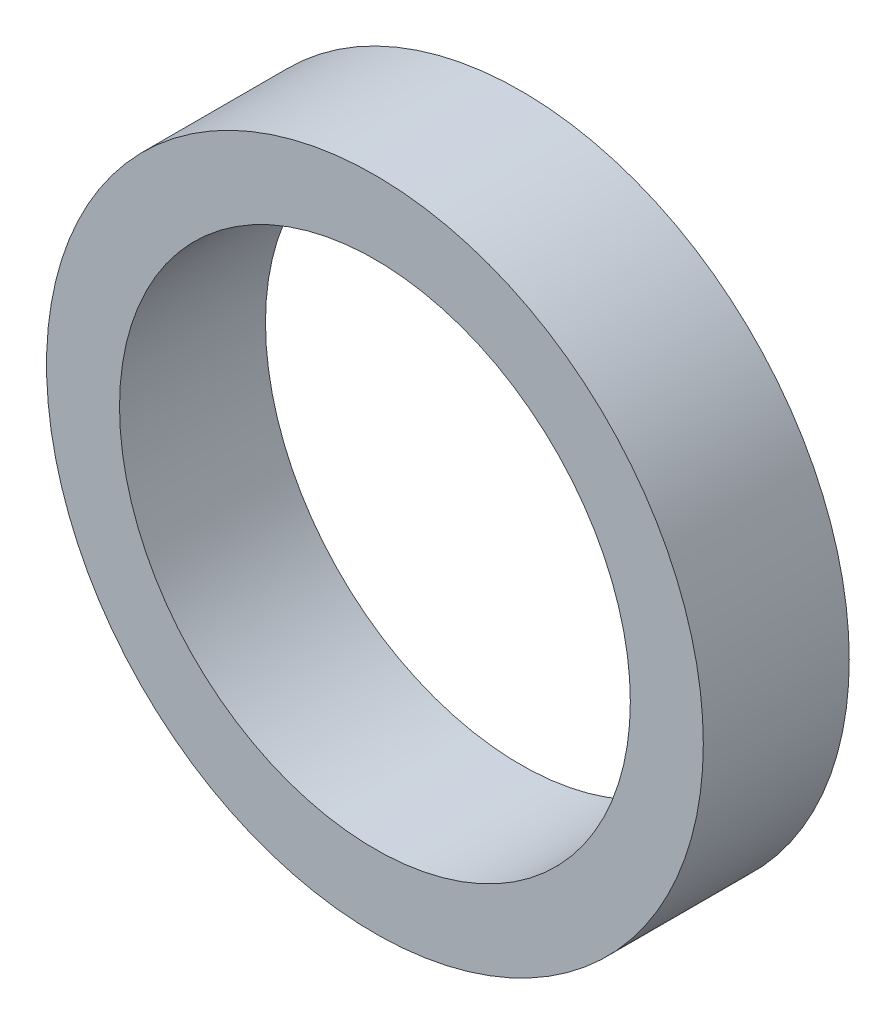
SolidWorks part; units mm, degrees
ref_plane "Спереди" through (0, 0, 0) normal (0, 0, 1) x (1, 0, 0)
ref_plane "Сверху" through (0, 0, 0) normal (0, 1, 0) x (1, 0, 0)
ref_plane "Справа" through (0, 0, 0) normal (1, 0, 0) x (0, 0, -1)
sketch "Эскиз1" plane through (0, 0, 0) normal (0, 0, 1) x (1, 0, 0)
  circle A0 centre (0, 0) radius 14
  circle A1 centre (0, 0) radius 18
  dimension "D1" = 28
  dimension "D2" = 36
extrude "Бобышка-Вытянуть1" add sketch "Эскиз1" along normal blind 8
